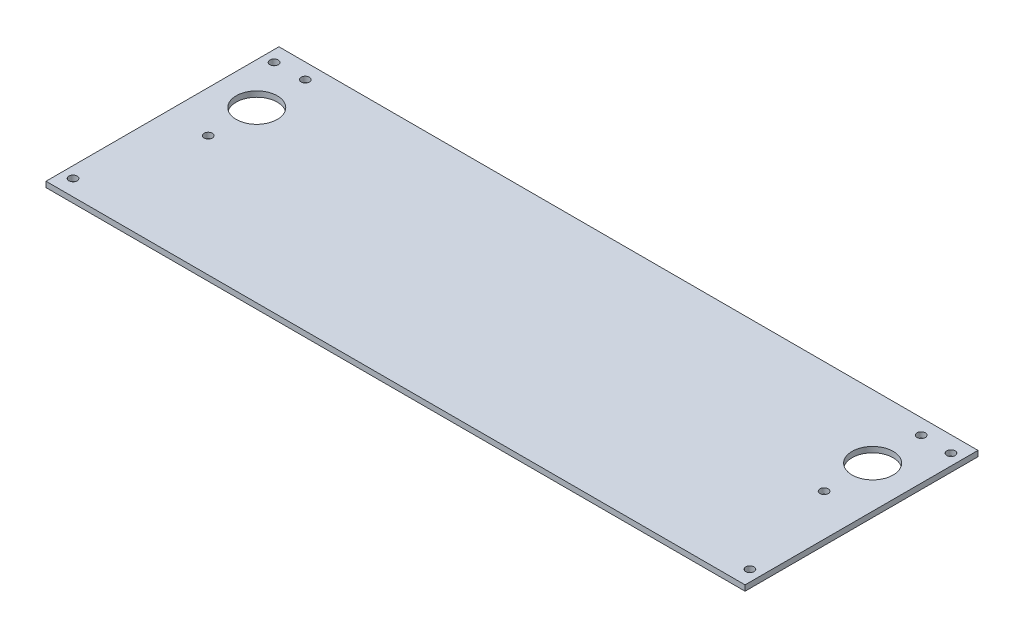
SolidWorks part; units mm, degrees
material "FR4"
ref_plane "前视基准面" through (0, 0, 0) normal (0, 0, 1) x (1, 0, 0)
ref_plane "上视基准面" through (0, 0, 0) normal (0, 1, 0) x (1, 0, 0)
ref_plane "右视基准面" through (0, 0, 0) normal (1, 0, 0) x (0, 0, -1)
sketch "草图1" plane through (0, 0, 0) normal (0, 1, 0) x (1, 0, 0)
  line L1 (126.05, -42) -> (-126.05, -42)
  line L2 (126.05, -42) -> (126.05, 42)
  line L3 (126.05, 42) -> (-126.05, 42)
  line L4 (-126.05, -42) -> (-126.05, 42)
  line L5 (126.05, -42) -> (-126.05, 42) construction
  line L6 (126.05, 42) -> (-126.05, -42) construction
  point P0 (0, 0)
  dimension "D1" = 252.1
  dimension "D2" = 84
extrude "凸台-拉伸1" add sketch "草图1" along normal mid plane 2
sketch "草图2" plane through (0, 1, 0) normal (0, 1, 0) x (1, 0, 0)
  line L0 (126.05, -42) -> (126.05, 42) construction
  line L1 (126.05, 29) -> (118.05, 29)
  line L2 (126.05, 29) -> (126.05, 9)
  line L3 (126.05, 9) -> (118.05, 9)
  line L4 (118.05, 29) -> (118.05, 9)
  line L5 (126.05, 19) -> (74.939, 19) construction
  line L6 (124.05, 29) -> (120.05, 29)
  line L7 (124.05, 29) -> (124.05, 34)
  line L8 (124.05, 34) -> (120.05, 34)
  line L9 (120.05, 29) -> (120.05, 34)
  line L10 (124.05, 9) -> (124.05, 4)
  line L11 (120.05, 9) -> (120.05, 4)
  line L12 (124.05, 4) -> (120.05, 4)
  line M12 (126.05, -42) -> (126.05, 42)
  dimension "D1" = 8
  dimension "D2" = 2
  dimension "D3" = 2
  dimension "D4" = 20
  dimension "D5" = 30
extrude "切除-拉伸1" [suppressed] cut sketch "草图2" against normal blind 10 contours L9 L1 L7 L8 | L5 L2 L1 L4 | L5 L4 L3 M12 | L12 L10 L3 L11
mirror "镜向1" [suppressed] about plane through (0, 0, 0) normal (1, 0, 0)
sketch "草图3" plane through (0, 1, 0) normal (0, 1, 0) x (1, 0, 0)
  line L1 (105.05, 26) -> (117.05, 26)
  line L2 (105.05, 26) -> (105.05, 12)
  line L3 (105.05, 12) -> (117.05, 12)
  line L4 (117.05, 26) -> (117.05, 12)
  line L5 (105.05, 26) -> (117.05, 12) construction
  line L6 (105.05, 12) -> (117.05, 26) construction
  circle A0 centre (111.05, 19) radius 4 construction
  dimension "D1" = 14
  dimension "D2" = 12
sketch "Sketch1" plane through (0, 1, 0) normal (0, 1, 0) x (1, 0, 0)
  line L0 (126.05, 42) -> (-126.05, 42) construction
  line L1 (-122.05, -36.25) -> (122.05, -36.25) construction
  line L2 (-122.05, -36.25) -> (-122.05, 36.25) construction
  line L3 (-122.05, 36.25) -> (122.05, 36.25) construction
  line L4 (122.05, -36.25) -> (122.05, 36.25) construction
  line L5 (-122.05, -36.25) -> (122.05, 36.25) construction
  line L6 (-122.05, 36.25) -> (122.05, -36.25) construction
  circle A0 centre (-122.05, 36.25) radius 1.5
  circle A1 centre (-122.05, -36.25) radius 1.5
  circle A2 centre (122.05, -36.25) radius 1.5
  circle A3 centre (122.05, 36.25) radius 1.5
  point P0 (0, 0)
  dimension "D3" = 3
  dimension "D1" = 244.1
  dimension "D2" = 5.75
extrude "Cut-Extrude1" cut sketch "Sketch1" against normal blind 10
sketch "Sketch2" plane through (0, 1, 0) normal (0, 1, 0) x (1, 0, 0)
  line L2 (0, 0) -> (0, 72.8508) construction
  line L3 (-126.05, 42) -> (-126.05, -42) construction
  line L4 (-126.05, 34) -> (-128.89, 34)
  line L5 (-126.05, 34) -> (-126.05, 4)
  line L6 (-126.05, 4) -> (-128.89, 4)
  line L7 (-132.89, 30) -> (-132.89, 8)
  line L8 (126.05, 42) -> (-126.05, 42) construction
  arc A0 (-128.89, 4) -> (-132.89, 8) centre (-128.89, 8) cw
  arc A1 (-132.89, 30) -> (-128.89, 34) centre (-128.89, 30) cw
  point P16 (-132.89, 4)
  point P19 (-132.89, 34)
  dimension "D4" = 4
  dimension "D1" = 8
  dimension "D2" = 6.84
  dimension "D3" = 30
extrude "Boss-Extrude1" [suppressed] add sketch "Sketch2" against normal blind 2
sketch "Sketch3" [suppressed] plane through (0, 1, 0) normal (0, 1, 0) x (1, 0, 0)
  line L0 (-126.05, 42) -> (-126.05, 34) construction
  line L1 (-128.39, 8.5) -> (-107.39, 8.5) construction
  line L2 (-128.39, 8.5) -> (-128.39, 29.5) construction
  line L3 (-128.39, 29.5) -> (-107.39, 29.5) construction
  line L4 (-107.39, 8.5) -> (-107.39, 29.5) construction
  line L5 (-128.39, 8.5) -> (-107.39, 29.5) construction
  line L6 (-128.39, 29.5) -> (-107.39, 8.5) construction
  line L8 (-132.89, 30) -> (-132.89, 8) construction
  circle A0 centre (-128.39, 29.5) radius 2
  circle A1 centre (-128.39, 8.5) radius 2
  circle A2 centre (-107.39, 8.5) radius 2
  circle A3 centre (-107.39, 29.5) radius 2
  point P0 (-117.89, 19)
  point P16 (-132.89, 19)
  dimension "D4" = 4
  dimension "D1" = 2.34
  dimension "D2" = 21
  dimension "D3" = 21
extrude "Cut-Extrude2" [suppressed] cut sketch "Sketch3" against normal blind 2
sketch "Sketch4" plane through (0, 1, 0) normal (0, 1, 0) x (1, 0, 0)
  circle A0 centre (-111.05, 19) radius 7 construction
  circle A1 centre (111.05, 19) radius 7 construction
  circle A6 centre (111.05, 19) radius 7 construction
  circle A7 centre (-111.05, 19) radius 7 construction
  circle A8 centre (-111.05, 19) radius 7.4
  circle A9 centre (111.05, 19) radius 7.4
  dimension "D1" = 0.4
extrude "Cut-Extrude3" cut sketch "Sketch4" against normal through all
sketch "Sketch5" plane through (0, 1, 0) normal (0, 1, 0) x (1, 0, 0)
  circle A0 centre (-111.05, 1.5) radius 1.5 construction
  circle A1 centre (-111.05, 36.5) radius 1.5 construction
  circle A2 centre (111.05, 1.5) radius 1.5 construction
  circle A3 centre (111.05, 36.5) radius 1.5 construction
  circle A4 centre (-111.05, 1.5) radius 1.5
  circle A5 centre (-111.05, 36.5) radius 1.5
  circle A6 centre (111.05, 1.5) radius 1.5
  circle A7 centre (111.05, 36.5) radius 1.5
extrude "Cut-Extrude4" cut sketch "Sketch5" against normal blind 10
